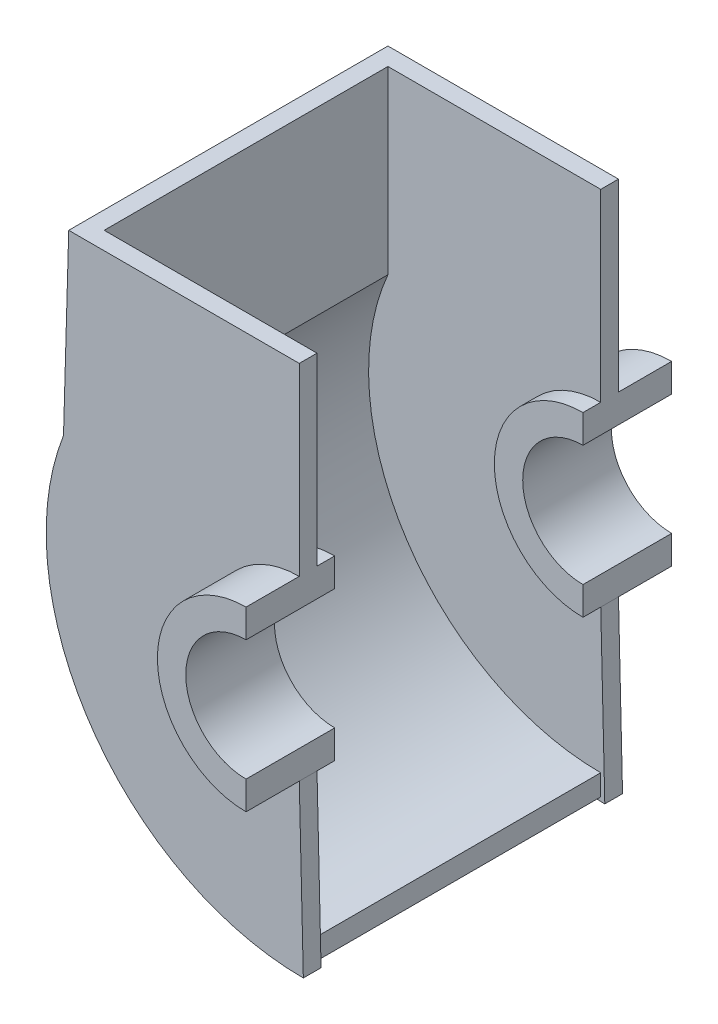
SolidWorks part; units mm, degrees
ref_plane "Front Plane" through (0, 0, 0) normal (0, 0, 1) x (1, 0, 0)
ref_plane "Top Plane" through (0, 0, 0) normal (0, 1, 0) x (1, 0, 0)
ref_plane "Right Plane" through (0, 0, 0) normal (1, 0, 0) x (0, 0, -1)
sketch "Sketch1" plane through (0, 0, 0) normal (0, 0, 1) x (1, 0, 0)
  line L0 (0, 635) -> (0, 431.8)
  line L1 (0, -431.8) -> (0, -635)
  arc A0 (0, 431.8) -> (0, -431.8) centre (0, 0) ccw
  arc A1 (0, 635) -> (0, -635) centre (0, 0) ccw
  dimension "D1" = 1270
  dimension "D2" = 863.6
extrude "Boss-Extrude1" add sketch "Sketch1" along normal blind 508 and the other way blind 127
sketch "Sketch3" plane through (0, 0, 0) normal (0, 0, 1) x (1, 0, 0)
  line L0 (0, -635) -> (29.0999, -1841.5)
  line L1 (0, 635) -> (0, 1955.8)
  line L2 (0, 1955.8) -> (-1651, 1955.8)
  line L3 (-1651, 1955.8) -> (-1688.4154, 664.2766)
  arc A0 (-1688.4154, 664.2766) -> (29.0999, -1841.5) centre (29.0999, 0) ccw
  arc A1 (0, 635) -> (0, -635) centre (29.0999, 0) ccw
  arc A2 (0, 635) -> (0, -635) centre (0, 0) ccw construction
  dimension "D1" = 3683
  dimension "D2" = 1320.8
  dimension "D3" = 1651
extrude "Boss-Extrude2" add sketch "Sketch3" along normal blind 127 contours A1 L1 L2 L3 A0 L0
ref_plane "Plane1" through (0, 0, -1016) normal (0, 0, 1) x (1, 0, 0)
mirror "Mirror1" about plane through (0, 0, -1016) normal (0, 0, 1) of bodies 102
sketch "Sketch4" plane through (0, 0, -2032) normal (0, 0, 1) x (1, 0, 0)
  line L0 (-1688.4154, 664.2766) -> (-1651, 1955.8)
  line L1 (-1651, 1955.8) -> (-1524, 1955.8)
  line L2 (0, -1662.4799) -> (0, -1812.4001)
  line L3 (0, 1955.8) -> (-1651, 1955.8) construction
  line L4 (-1524, 1955.8) -> (-1524, 664.2766)
  arc A2 (-1524, 664.2766) -> (0, -1662.4799) centre (0, 0) ccw
  dimension "D1" = 127
extrude "Extrude-Thin1" add sketch "Sketch4" along normal up to surface (2032 mm away) thin
